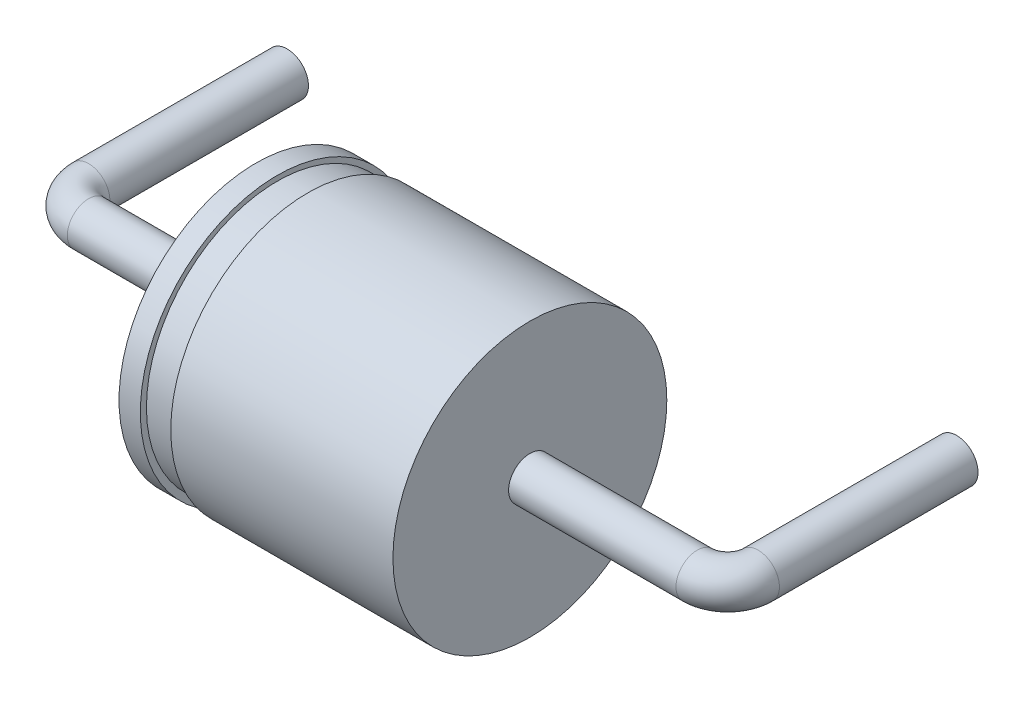
SolidWorks part; units mm, degrees
ref_plane "Front" through (0, 0, 0) normal (0, 0, 1) x (1, 0, 0)
ref_plane "Top" through (0, 0, 0) normal (0, 1, 0) x (1, 0, 0)
ref_plane "Right" through (0, 0, 0) normal (1, 0, 0) x (0, 0, -1)
ref_plane "Плоскость1" through (6.5, 0, 0) normal (1, 0, 0) x (0, 0, -1)
sketch "Эскиз3" plane through (6.5, 0, 0) normal (1, 0, 0) x (0, 0, -1)
  circle A0 centre (-1.525, -0.0336) radius 4.5
  dimension "D2" = 9
  dimension "D1" = 1.525
extrude "Вытянуть1" add sketch "Эскиз3" along normal blind 9
sketch "Эскиз4" plane through (0, 0, 0) normal (0, 1, 0) x (1, 0, 0)
  line L0 (0, -1.525) -> (10.3423, -1.525) construction
  line L1 (15.5, 2.975) -> (6.5, 2.975) construction
  line L2 (6.5, -6.025) -> (15.5, -6.025) construction
  line L3 (7.2, 3.075) -> (8.2, 3.075)
  line L4 (7.2, 3.075) -> (7.2, 2.775)
  line L5 (7.2, 2.775) -> (8.2, 2.775)
  line L6 (8.2, 3.075) -> (8.2, 2.775)
  dimension "D1" = 4.3
  dimension "D2" = 7.2
  dimension "D3" = 1
  dimension "D4" = 0.3
revolve "Вырез-Повернуть1" cut sketch "Эскиз4" angle 360 about L0
sketch "Эскиз5" plane through (0, 0, 0) normal (0, 1, 0) x (1, 0, 0)
  line L0 (0, 0) -> (0, -0.525)
  line L1 (7.2, -1.525) -> (6.5, -1.525) construction
  line L2 (1, -1.525) -> (6.8, -1.525)
  line L3 (11, 0.7069) -> (11, -3.9976) construction
  line L4 (21, -1.525) -> (6.8, -1.525)
  line L5 (22, 0) -> (22, -0.525)
  arc A0 (0, -0.525) -> (1, -1.525) centre (1, -0.525) ccw
  arc A1 (21, -1.525) -> (22, -0.525) centre (21, -0.525) ccw
  point P12 (0, -1.525)
  point P15 (22, -1.525)
  dimension "D2" = 1
  dimension "D3" = 1
  dimension "D1" = 22
sketch "Эскиз6" plane through (0, 0, 0) normal (0, 0, 1) x (1, 0, 0)
  line L0 (11, -1.599) -> (11, 5.2204) construction
  line L7 (6.5, 4.4664) -> (6.5, -4.5336) construction
  line L8 (15.5, -4.5336) -> (15.5, 4.4664) construction
  circle A0 centre (0, 0) radius 0.7
  circle A1 centre (22, 0) radius 0.7
  dimension "D1" = 22
  dimension "D2" = 1.4
  dimension "D3" = 1.4
sketch "Эскиз7" plane through (0, 0, 0) normal (0, 0, 1) x (1, 0, 0)
  circle A0 centre (0, 0) radius 0.7
  dimension "D1" = 1.4
extrude "Вытянуть2" add sketch "Эскиз6" against normal blind 6
sweep "По траектории1" add profiles "Эскиз7" path "Эскиз5"
